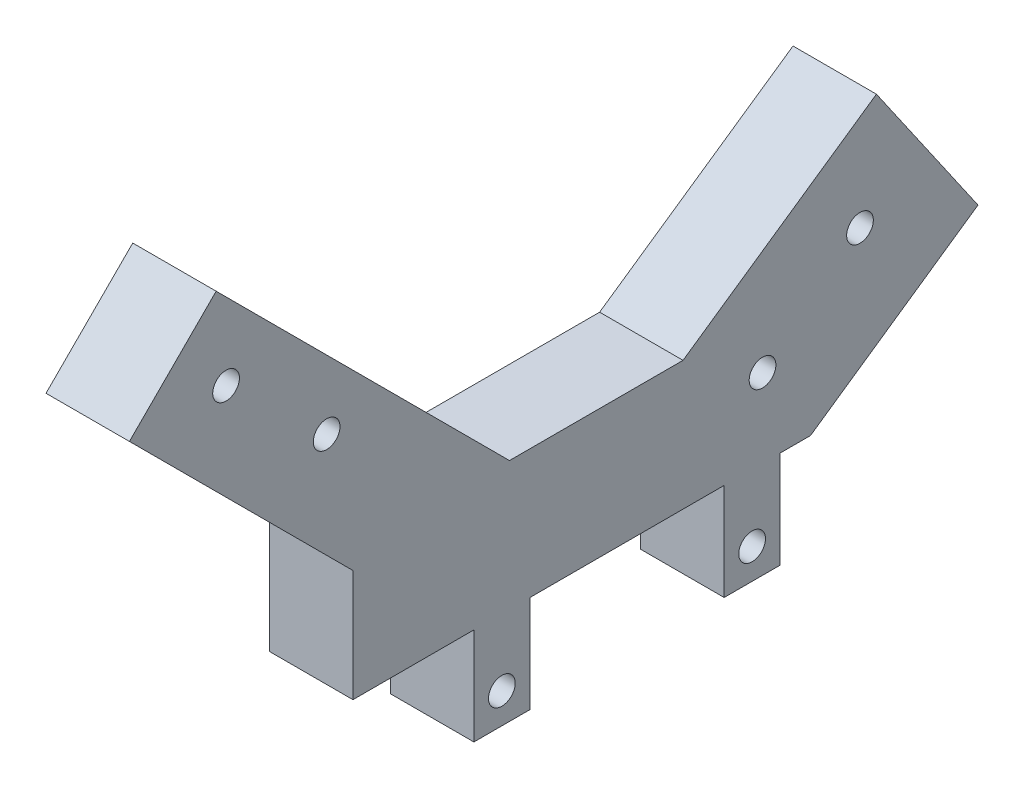
SolidWorks part; units mm, degrees
ref_plane "前视基准面" through (0, 0, 0) normal (0, 0, 1) x (1, 0, 0)
ref_plane "上视基准面" through (0, 0, 0) normal (0, 1, 0) x (1, 0, 0)
ref_plane "右视基准面" through (0, 0, 0) normal (1, 0, 0) x (0, 0, -1)
sketch "草图1" plane through (0, 0, 0) normal (1, 0, 0) x (0, 0, -1)
  line L7 (11.649, -4) -> (18.351, -15.6389) construction
  line L8 (-11.649, -15.6389) -> (-18.351, -15.6389)
  line L9 (-11.649, -15.6389) -> (-11.649, -4)
  line L11 (-18.351, -15.6389) -> (-18.351, -4)
  line L12 (-11.649, -15.6389) -> (-18.351, -4) construction
  line L13 (-11.649, -4) -> (-18.351, -15.6389) construction
  line L14 (11.649, -15.6389) -> (18.351, -4) construction
  line L15 (18.351, -15.6389) -> (18.351, -4)
  line L16 (11.649, -15.6389) -> (11.649, -4)
  line L17 (11.649, -15.6389) -> (18.351, -15.6389)
  line L18 (-11.649, -4) -> (11.649, -4)
  line L20 (6.7187, 11.4487) -> (-14.0865, 11.4487)
  line L21 (-14.0865, 11.4487) -> (-49.2481, 46.6103)
  line L22 (-49.2481, 46.6103) -> (-59.6467, 36.2116)
  line L25 (-32.8484, -4) -> (-18.351, -4)
  line L31 (18.351, -4) -> (22.0013, -4)
  line L32 (-59.6467, 36.2116) -> (-32.8484, 9.4133)
  line L33 (-32.8484, 9.4133) -> (-32.8484, -4)
  line L34 (6.7187, 11.4487) -> (29.903, 27.4895)
  line L35 (29.903, 27.4895) -> (42.0788, 9.8913)
  line L36 (42.0788, 9.8913) -> (22.0013, -4)
  circle A0 centre (-15, -12) radius 1.6
  circle A2 centre (15, -12) radius 1.6
  circle A3 centre (-48.0605, 36.2116) radius 1.6
  circle A4 centre (-36.0024, 25.1432) radius 1.6
  circle A5 centre (16.2492, 5.4119) radius 1.6
  circle A6 centre (27.9317, 14.6001) radius 1.6
  point P1 (45.8251, 15.055)
  point P4 (29.903, 27.4895)
  point P5 (27.9317, 14.6001)
extrude "凸台-拉伸1" add sketch "草图1" along normal blind 10
